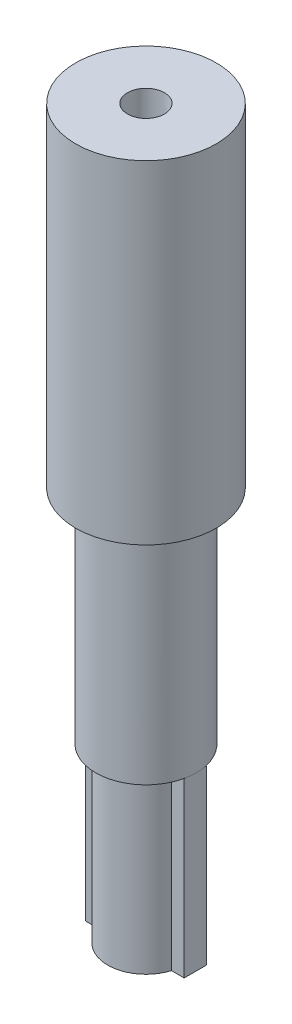
SolidWorks part; units mm, degrees
ref_plane "Front Plane" through (0, 0, 0) normal (0, 0, 1) x (1, 0, 0)
ref_plane "Top Plane" through (0, 0, 0) normal (0, 1, 0) x (1, 0, 0)
ref_plane "Right Plane" through (0, 0, 0) normal (1, 0, 0) x (0, 0, -1)
sketch "Sketch1" plane through (0, 0, 0) normal (0, 1, 0) x (1, 0, 0)
  line L1 (-4, 0.9) -> (4, 0.9)
  line L2 (-4, 0.9) -> (-4, -0.9)
  line L3 (-4, -0.9) -> (4, -0.9)
  line L4 (4, 0.9) -> (4, -0.9)
  line L5 (-4, 0.9) -> (4, -0.9) construction
  line L6 (-4, -0.9) -> (4, 0.9) construction
  circle A0 centre (0, 0) radius 3.1
  dimension "D1" = 6.2
  dimension "D2" = 1.8
  dimension "D3" = 8
extrude "Boss-Extrude1" add sketch "Sketch1" along normal blind 14
sketch "Sketch2" plane through (0, 14, 0) normal (0, 1, 0) x (1, 0, 0)
  circle A0 centre (0, 0) radius 4.075
  dimension "D1" = 8.15
extrude "Boss-Extrude2" add sketch "Sketch2" along normal blind 18
sketch "Sketch3" plane through (0, 32, 0) normal (0, 1, 0) x (1, 0, 0)
  circle A0 centre (0, 0) radius 5.7
  dimension "D1" = 11.4
extrude "Boss-Extrude3" add sketch "Sketch3" along normal blind 2
sketch "Sketch4" plane through (0, 34, 0) normal (0, 1, 0) x (1, 0, 0)
  circle A0 centre (0, 0) radius 5.7
  dimension "D1" = 11.4
extrude "Boss-Extrude4" add sketch "Sketch4" along normal blind 25
sketch "Sketch5" plane through (0, 59, 0) normal (0, 1, 0) x (1, 0, 0)
  circle A0 centre (0, 0) radius 1.5
  dimension "D1" = 3
extrude "Cut-Extrude1" cut sketch "Sketch5" against normal blind 17
